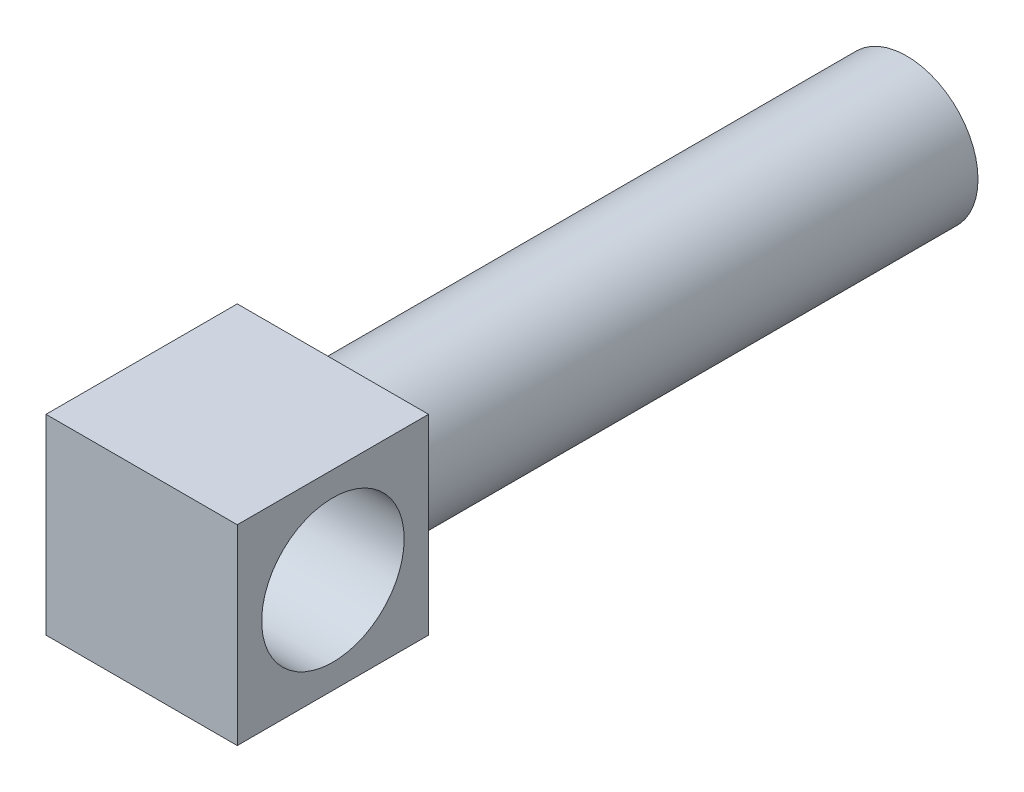
SolidWorks part; units mm, degrees
ref_plane "Front Plane" through (0, 0, 0) normal (0, 0, 1) x (1, 0, 0)
ref_plane "Top Plane" through (0, 0, 0) normal (0, 1, 0) x (1, 0, 0)
ref_plane "Right Plane" through (0, 0, 0) normal (1, 0, 0) x (0, 0, -1)
sketch "Sketch1" plane through (0, 0, 0) normal (0, 0, 1) x (1, 0, 0)
  circle A0 centre (18.9979, 14.0341) radius 7.45
  dimension "D1" = 14.9
extrude "Boss-Extrude1" add sketch "Sketch1" along normal blind 60
sketch "Sketch2" plane through (0, 0, 60) normal (0, 0, 1) x (1, 0, 0)
  line L0 (18.9979, 24.0341) -> (18.9979, 4.0341) construction
  line L1 (8.9979, 24.0341) -> (28.9979, 24.0341)
  line L2 (8.9979, 24.0341) -> (8.9979, 4.0341)
  line L3 (8.9979, 4.0341) -> (28.9979, 4.0341)
  line L4 (28.9979, 24.0341) -> (28.9979, 4.0341)
  line L5 (8.9979, 14.0341) -> (28.9979, 14.0341) construction
  line L6 (18.9979, 21.4841) -> (18.9979, 6.5841) construction
  line L7 (11.5479, 14.0341) -> (26.4479, 14.0341) construction
  circle A0 centre (18.9979, 14.0341) radius 7.45 construction
  point P8 (18.9979, 14.0341)
  point P16 (18.9979, 14.0341)
  dimension "D1" = 20
extrude "Boss-Extrude2" add sketch "Sketch2" along normal blind 20
sketch "Sketch3" plane through (28.9979, 0, 0) normal (1, 0, 0) x (0, 0, -1)
  line L0 (-80, 4.0341) -> (-80, 24.0341) construction
  line L2 (-80, 24.0341) -> (-60, 24.0341) construction
  circle A0 centre (-70, 14.0341) radius 7.45
  point P6 (-75.3697, 30.1461)
  dimension "D1" = 14.9
  dimension "D2" = 10
  dimension "D3" = 10
extrude "Cut-Extrude1" cut sketch "Sketch3" against normal through all
